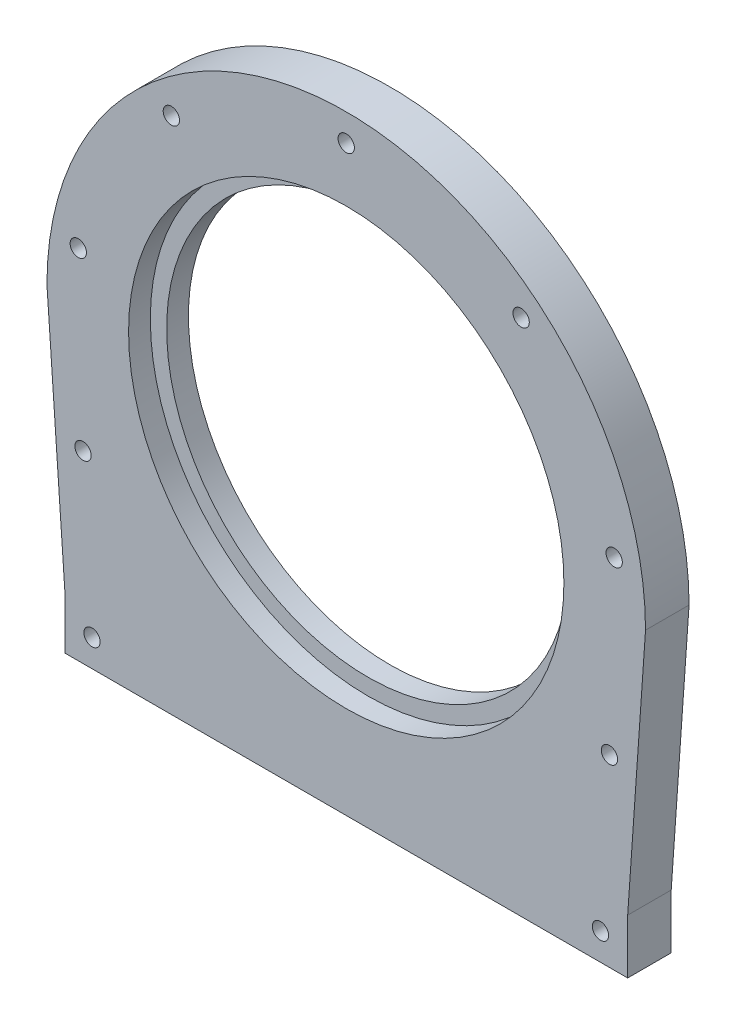
SolidWorks part; units mm, degrees
ref_plane "Front Plane" through (0, 0, 0) normal (0, 0, 1) x (1, 0, 0)
ref_plane "Top Plane" through (0, 0, 0) normal (0, 1, 0) x (1, 0, 0)
ref_plane "Right Plane" through (0, 0, 0) normal (1, 0, 0) x (0, 0, -1)
sketch "Sketch1" plane through (0, 0, 0) normal (0, 0, 1) x (1, 0, 0)
  line L7 (-51.7191, -57) -> (-41.6948, -57)
  line L8 (41.6948, -57) -> (-41.6948, -57)
  line L9 (41.6948, -57) -> (51.7191, -57)
  line L10 (-51.7191, -47) -> (-51.7191, -57)
  line L11 (51.7191, -57) -> (51.7191, -47)
  line L12 (-51.7191, -47) -> (-55, 0)
  line L13 (51.7191, -47) -> (55, 0)
  circle A12 centre (46.7191, -52) radius 1.5
  circle A13 centre (48.3717, -23.1518) radius 1.5
  circle A14 centre (49.2404, 8.6824) radius 1.5
  circle A15 centre (32.1394, 38.3022) radius 1.5
  circle A16 centre (0, 50) radius 1.5
  circle A17 centre (-32.1394, 38.3022) radius 1.5
  circle A18 centre (-49.2404, 8.6824) radius 1.5
  circle A19 centre (-48.3717, -23.1518) radius 1.5
  circle A20 centre (-46.7191, -52) radius 1.5
  arc A21 (55, 0) -> (-55, 0) centre (0, 0) ccw
  circle A22 centre (0, 0) radius 40
  circle A23 centre (0, 0) radius 37
extrude "Boss-Extrude1" add sketch "Sketch1" along normal blind 8 contours A22 A23 | L13 A21 L12 L10 L7 L8 L9 L11 A22 A12 A13 A14 A15 A16 A17 A18 A19 A20
sketch "Sketch3" plane through (0, 0, 8) normal (0, 0, 1) x (1, 0, 0)
  circle A0 centre (0, 0) radius 40
extrude "Cut-Extrude1" cut sketch "Sketch3" against normal blind 4
sketch "Sketch4" plane through (0, 0, 0) normal (0, 0, -1) x (-1, 0, 0)
  circle A0 centre (46.7191, -52) radius 1.5 construction
  circle A1 centre (48.3717, -23.1518) radius 1.5 construction
  circle A2 centre (49.2404, 8.6824) radius 1.5 construction
  circle A3 centre (32.1394, 38.3022) radius 1.5 construction
  circle A4 centre (0, 50) radius 1.5 construction
  circle A5 centre (-32.1394, 38.3022) radius 1.5 construction
  circle A6 centre (-49.2404, 8.6824) radius 1.5 construction
  circle A7 centre (-48.3717, -23.1518) radius 1.5 construction
  circle A8 centre (-46.7191, -52) radius 1.5 construction
  circle A9 centre (46.7191, -52) radius 1.5
  circle A10 centre (48.3717, -23.1518) radius 1.5
  circle A11 centre (49.2404, 8.6824) radius 1.5
  circle A12 centre (32.1394, 38.3022) radius 1.5
  circle A13 centre (0, 50) radius 1.5
  circle A14 centre (-32.1394, 38.3022) radius 1.5
  circle A15 centre (-49.2404, 8.6824) radius 1.5
  circle A16 centre (-48.3717, -23.1518) radius 1.5
  circle A17 centre (-46.7191, -52) radius 1.5
  circle A18 centre (-46.7191, -52) radius 3
  circle A19 centre (-48.3717, -23.1518) radius 3
  circle A20 centre (-49.2404, 8.6824) radius 3
  circle A21 centre (-32.1394, 38.3022) radius 3
  circle A22 centre (0, 50) radius 3
  circle A23 centre (32.1394, 38.3022) radius 3
  circle A24 centre (49.2404, 8.6824) radius 3
  circle A25 centre (48.3717, -23.1518) radius 3
  circle A26 centre (46.7191, -52) radius 3
  dimension "D1" = 1.5
extrude "Cut-Extrude2" cut sketch "Sketch4" against normal blind 4
